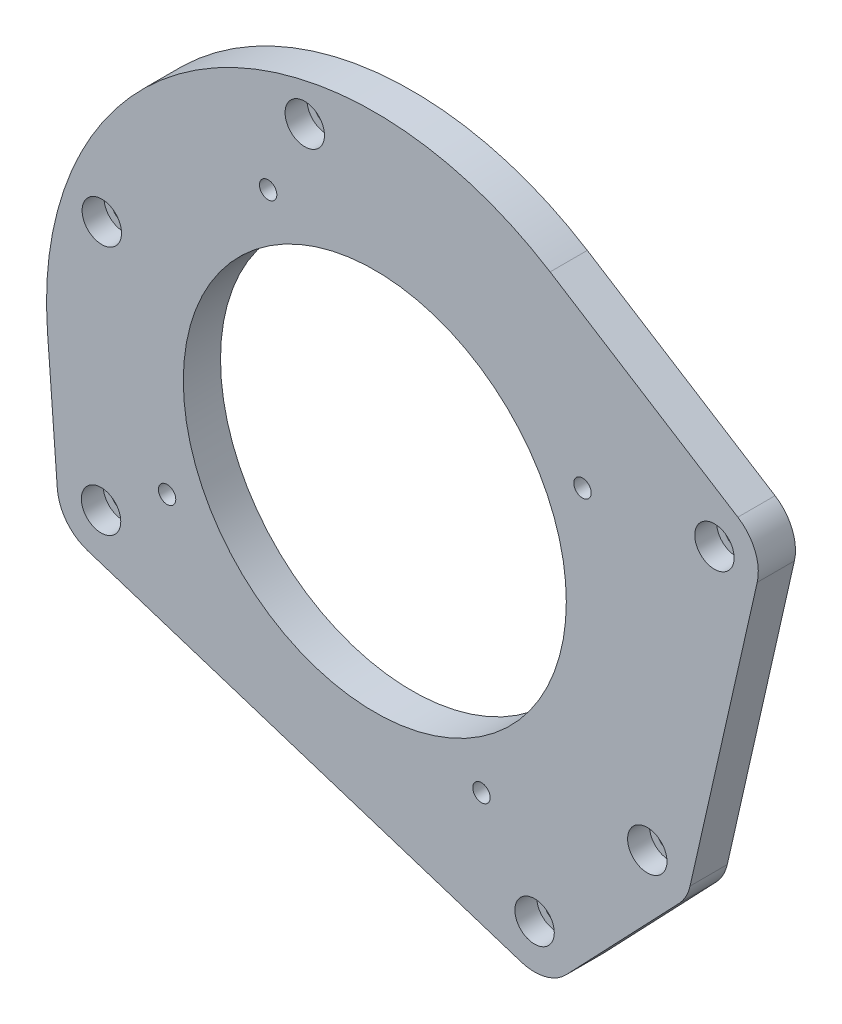
SolidWorks part; units mm, degrees
ref_plane "Front Plane" through (0, 0, 0) normal (0, 0, 1) x (1, 0, 0)
ref_plane "Top Plane" through (0, 0, 0) normal (0, 1, 0) x (1, 0, 0)
ref_plane "Right Plane" through (0, 0, 0) normal (1, 0, 0) x (0, 0, -1)
sketch "Sketch1" plane through (0, 0, 0) normal (0, 0, 1) x (1, 0, 0)
  line L0 (-125.0635, -70.0468) -> (73, -133.7177) construction
  line L1 (-131.1964, -89.1247) -> (66.8671, -152.7956)
  line L2 (-124.7345, 44.2324) -> (-125.0635, -70.0468) construction
  line L3 (-124.7345, 44.2324) -> (-32, 129.3011) construction
  line L4 (-32, 129.3011) -> (155.1738, 55.7151) construction
  line L5 (155.1738, 55.7151) -> (124.5, -79.7769) construction
  line L6 (124.5, -79.7769) -> (73, -133.7177) construction
  line L7 (-145.0467, -71.5483) -> (-149.5783, -11.2395)
  line L8 (165.8734, 72.6591) -> (80.0893, 126.8294)
  line L9 (174.7187, 51.2904) -> (144.0449, -84.2016)
  line L10 (87.4942, -147.556) -> (138.9942, -93.6152)
  circle A0 centre (-125.0635, -70.0468) radius 4
  circle A1 centre (73, -133.7177) radius 4
  circle A2 centre (124.5, -79.7769) radius 4
  circle A3 centre (155.1738, 55.7151) radius 4
  circle A4 centre (-32, 129.3011) radius 4
  circle A5 centre (0, 0) radius 87.5
  circle A6 centre (-124.7345, 44.2324) radius 4
  circle A8 centre (0, 0) radius 125 construction
  arc A10 (66.8671, -152.7956) -> (87.4942, -147.556) centre (73, -133.7177) ccw
  arc A11 (-145.0467, -71.5483) -> (-131.1964, -89.1247) centre (-125.0635, -70.0468) ccw
  arc A13 (174.7187, 51.2904) -> (165.8734, 72.6591) centre (155.1738, 55.7151) ccw
  arc A14 (80.0893, 126.8294) -> (-149.5783, -11.2395) centre (0, 0) ccw
  arc A16 (138.9942, -93.6152) -> (144.0449, -84.2016) centre (124.5, -79.7769) ccw
  point P29 (166.1298, 72.4964)
  point P30 (166.4265, 72.3462)
  dimension "D13" = 175
  dimension "D14" = 250
  dimension "D15" = 8
  dimension "D1" = 124.7345
  dimension "D2" = 44.2324
  dimension "D3" = 125.0635
  dimension "D4" = 70.0468
  dimension "D5" = 73
  dimension "D6" = 133.7177
  dimension "D7" = 124.5
  dimension "D8" = 79.7769
  dimension "D9" = 55.7151
  dimension "D10" = 155.1738
  dimension "D11" = 129.3011
  dimension "D12" = 32
extrude "Boss-Extrude1" add sketch "Sketch1" along normal blind 17
hole_wizard "CBORE for M10 SHCS1" positions "3DSketch3" profile "Sketch5" counterbore size "M10" standard "ANSI Metric" end condition through all
sketch3d "3DSketch3"
  line L0 (-124.7345, 44.2324, 17) -> (-124.7345, 44.2324, 0) construction
  line L1 (-32, 129.3011, 17) -> (-32, 129.3011, 0) construction
  line L2 (155.1738, 55.7151, 17) -> (155.1738, 55.7151, 0) construction
  line L3 (124.5, -79.7769, 17) -> (124.5, -79.7769, 0) construction
  line L4 (73, -133.7177, 17) -> (73, -133.7177, 0) construction
  line L5 (-125.0635, -70.0468, 17) -> (-125.0635, -70.0468, 0) construction
  point P0 (-124.7345, 44.2324, 17)
  point P4 (-32, 129.3011, 17)
  point P8 (155.1738, 55.7151, 17)
  point P12 (124.5, -79.7769, 17)
  point P16 (73, -133.7177, 17)
  point P20 (-125.0635, -70.0468, 17)
sketch "Sketch5" plane through (-124.7345, 44.2324, 17) normal (1, 0, 0) x (0, -1, 0)
  line L0 (0, 0) -> (0, 17)
  line L1 (0, 17) -> (5.5, 17)
  line L3 (5.5, 17) -> (5.5, 10)
  line L4 (5.5, 10) -> (9, 10)
  line L5 (9, 10) -> (9, 0)
  line L7 (9, 0) -> (0, 0)
  line L11 (0, -6.35) -> (0, 107.95) construction
  dimension "Thru Hole Dia." = 11
  dimension "Thru Hole Depth" = 17
  dimension "C'Bore Dia." = 18
  dimension "C'Bore Depth" = 10
sketch "Sketch6" plane through (0, 0, 17) normal (0, 0, 1) x (1, 0, 0)
  line L0 (0, 0) -> (32.6486, 101.5613) construction
  line L1 (-131.1964, -89.1247) -> (66.8671, -152.7956) construction
  circle A0 centre (0, 0) radius 106.68 construction
  circle A1 centre (32.6486, 101.5613) radius 4.6161
  circle A2 centre (94.9007, 48.7286) radius 4.6161
  circle A3 centre (101.5613, -32.6486) radius 4.6161
  circle A4 centre (48.7286, -94.9007) radius 4.6161
  circle A5 centre (-32.6486, -101.5613) radius 4.6161
  circle A6 centre (-94.9007, -48.7286) radius 4.6161
  circle A7 centre (-101.5613, 32.6486) radius 4.6161
  circle A8 centre (-48.7286, 94.9007) radius 4.6161
  point P5 (32.6486, 101.5613)
  point P23 (0, 0)
  dimension "D1" = 213.36
hole_wizard "3/8-16 Tapped Hole3" positions "3DSketch4" profile "Sketch7" tap size "3/8-16" standard "ANSI Inch" end condition through all
sketch3d "3DSketch4"
  point P0 (-48.7286, 94.9007, 17)
  point P3 (94.9007, 48.7286, 17)
  point P6 (48.7286, -94.9007, 17)
  point P9 (-94.9007, -48.7286, 17)
sketch "Sketch7" plane through (-48.7286, 94.9007, 17) normal (1, 0, 0) x (0, -1, 0)
  line L0 (0, 0) -> (0, 17)
  line L1 (0, 17) -> (3.9687, 17)
  line L2 (3.9687, 17) -> (3.9687, 0)
  line L5 (3.9687, 0) -> (0, 0)
  line L11 (0, -6.35) -> (0, 107.95) construction
  dimension "Thru Tap Drill Dia." = 7.9375
  dimension "Thru Tap Drill Depth" = 17
cosmetic thread "Hole Thread14" parameters "D2"=9.525
cosmetic thread "Hole Thread15" parameters "D2"=9.525
cosmetic thread "Hole Thread16" parameters "D2"=9.525
cosmetic thread "Hole Thread17" parameters "D2"=9.525
